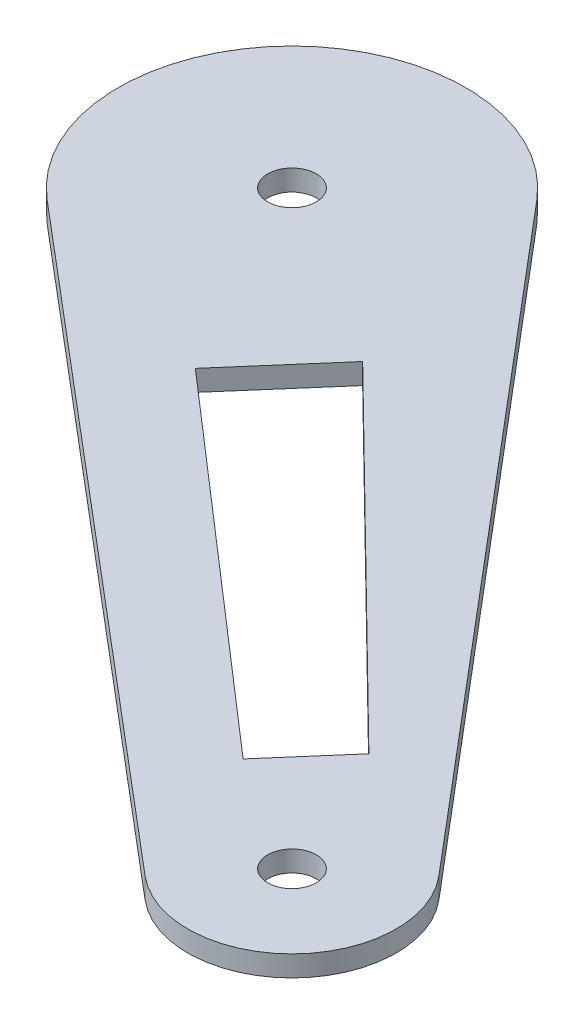
SolidWorks part; units mm, degrees
ref_plane "前视基准面" through (0, 0, 0) normal (0, 0, 1) x (1, 0, 0)
ref_plane "上视基准面" through (0, 0, 0) normal (0, 1, 0) x (1, 0, 0)
ref_plane "右视基准面" through (0, 0, 0) normal (1, 0, 0) x (0, 0, -1)
other "Configuration Table"
sketch "草图2" plane through (0, 0, 0) normal (0, 1, 0) x (1, 0, 0)
  line L0 (-140.5033, 0) -> (6884.6605, 0) construction
  line L1 (0, -140.5033) -> (0, 6884.6605) construction
  line L2 (0, 0) -> (42.4264, -42.4264)
  line L3 (42.4264, -42.4264) -> (-42.4264, 42.4264)
  line L4 (-58.5694, 23.3371) -> (32.7406, -53.88)
  line L5 (-23.3371, 58.5694) -> (53.88, -32.7406)
  circle A0 centre (-42.4264, 42.4264) radius 25
  circle A1 centre (42.4264, -42.4264) radius 15
  dimension "D3" = 50
  dimension "D4" = 30
  dimension "D1" = 60
  dimension "D2" = 120
extrude "凸台-拉伸2" add sketch "草图2" along normal blind 3
sketch "草图4" plane through (0, 3, 0) normal (0, 1, 0) x (1, 0, 0)
  line L0 (-58.5694, 23.3371) -> (32.7406, -53.88)
  line L1 (-58.5694, 23.3371) -> (32.7406, -53.88) construction
  line L2 (-23.3371, 58.5694) -> (53.88, -32.7406)
  line L3 (-23.3371, 58.5694) -> (53.88, -32.7406) construction
  line L4 (-56.6323, 25.6278) -> (34.6777, -51.5893)
  line L5 (-25.6278, 56.6323) -> (51.5893, -34.6777)
  circle A0 centre (-42.4264, 42.4264) radius 25
  circle A1 centre (42.4264, -42.4264) radius 15
  circle A2 centre (-42.4264, 42.4264) radius 22
  circle A3 centre (42.4264, -42.4264) radius 12
  circle A4 centre (-42.4264, 42.4264) radius 2.25
  circle A5 centre (42.4264, -42.4264) radius 2.5
  point P26 (0, 0)
  dimension "D3" = 4.5
  dimension "D4" = 5
  dimension "D1" = 3
  dimension "D2" = 3
extrude "切除-拉伸2" cut sketch "草图4" against normal through all contours A4 | A5
sketch "草图6" plane through (0, 3, 0) normal (0, 1, 0) x (1, 0, 0)
  circle A0 centre (-42.4264, 42.4264) radius 3.5
  dimension "D1" = 7
extrude "切除-拉伸3" cut sketch "草图6" against normal through all
sketch "草图7" plane through (0, 3, 0) normal (0, 1, 0) x (1, 0, 0)
  circle A0 centre (42.4264, -42.4264) radius 3.5
  dimension "D1" = 7
extrude "切除-拉伸4" cut sketch "草图7" against normal through all
sketch "草图8" plane through (0, 3, 0) normal (0, 1, 0) x (1, 0, 0)
  line L0 (-11.8521, 30.3069) -> (-26.8914, 12.9805)
  line L1 (-26.8914, 12.9805) -> (25.2188, -32.2512)
  line L2 (25.2188, -32.2512) -> (33.6267, -22.5647)
  line L3 (33.6267, -22.5647) -> (-15.703, 25.8704)
extrude "切除-拉伸5" cut sketch "草图8" against normal through all contours L2 L3 L0 L1
